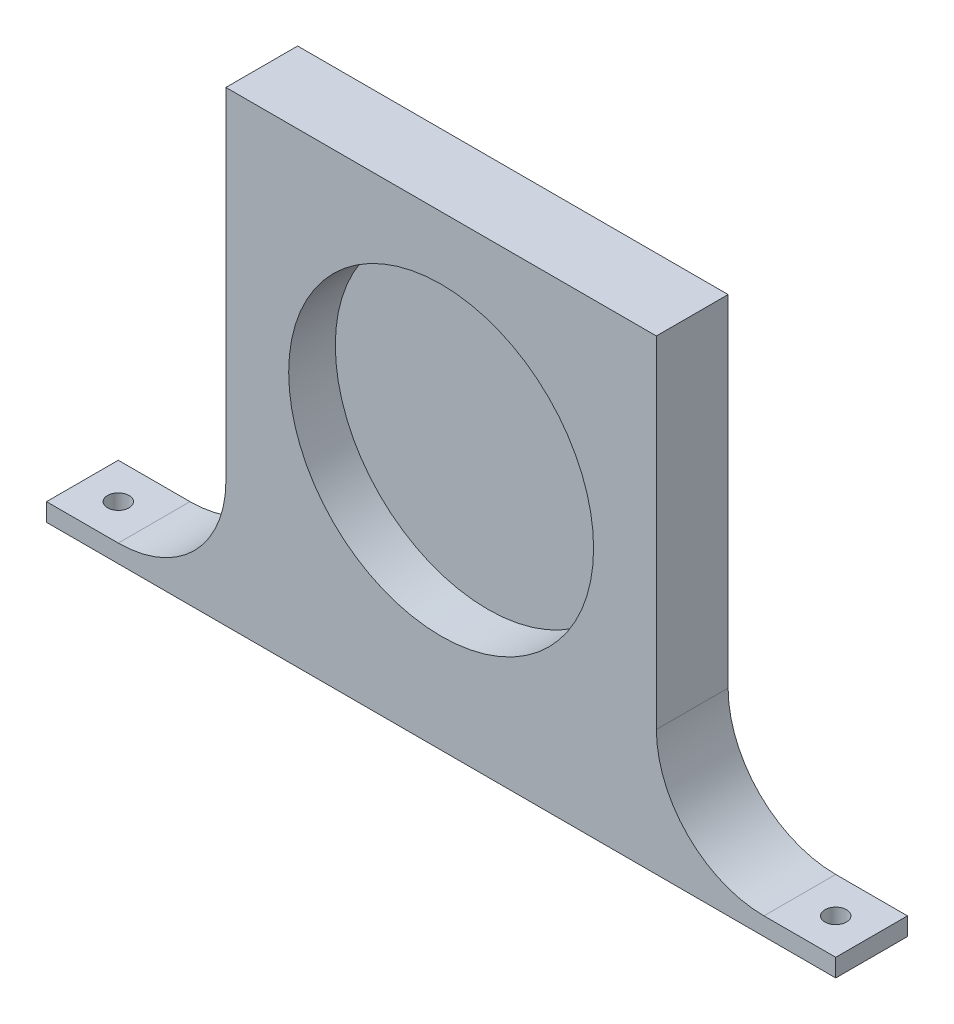
SolidWorks part; units mm, degrees
ref_plane "前视基准面" through (0, 0, 0) normal (0, 0, 1) x (1, 0, 0)
ref_plane "上视基准面" through (0, 0, 0) normal (0, 1, 0) x (1, 0, 0)
ref_plane "右视基准面" through (0, 0, 0) normal (1, 0, 0) x (0, 0, -1)
other "Configuration Table"
sketch "草图1" plane through (0, 0, 0) normal (0, 0, 1) x (1, 0, 0)
  line L1 (-60, 65) -> (60, 65)
  line L2 (-60, 65) -> (-60, -65)
  line L3 (-60, -65) -> (60, -65)
  line L4 (60, 65) -> (60, -65)
  line L5 (-60, 65) -> (60, -65) construction
  line L6 (-60, -65) -> (60, 65) construction
  point P0 (0, 0)
  dimension "D1" = 130
  dimension "D2" = 120
extrude "凸台-拉伸1" add sketch "草图1" along normal blind 20
sketch "草图2" plane through (0, 0, 20) normal (0, 0, 1) x (1, 0, 0)
  circle A0 centre (0, 5) radius 42.5
extrude "切除-拉伸1" cut sketch "草图2" against normal blind 13
sketch "草图4" plane through (0, -65, 0) normal (0, -1, 0) x (1, 0, 0)
  line L0 (60, 20) -> (110, 20)
  line L1 (60, 0) -> (110, 0)
  line L2 (110, 0) -> (110, 20)
  line L3 (60, 20) -> (60, 0)
extrude "凸台-拉伸2" add sketch "草图4" against normal blind 5
fillet "圆角2" radius 30 1 edges at (60, -60, 10)
mirror "镜向4" about plane through (0, 0, 0) normal (1, 0, 0) of "凸台-拉伸2"
fillet "圆角3" radius 30 1 edges at (-60, -60, 10)
sketch "草图5" plane through (0, -60, 0) normal (0, 1, 0) x (1, 0, 0)
  circle A0 centre (99.998, -10) radius 3
extrude "切除-拉伸2" cut sketch "草图5" against normal through all
mirror "镜向6" about plane through (0, 0, 0) normal (1, 0, 0) of "切除-拉伸2"
